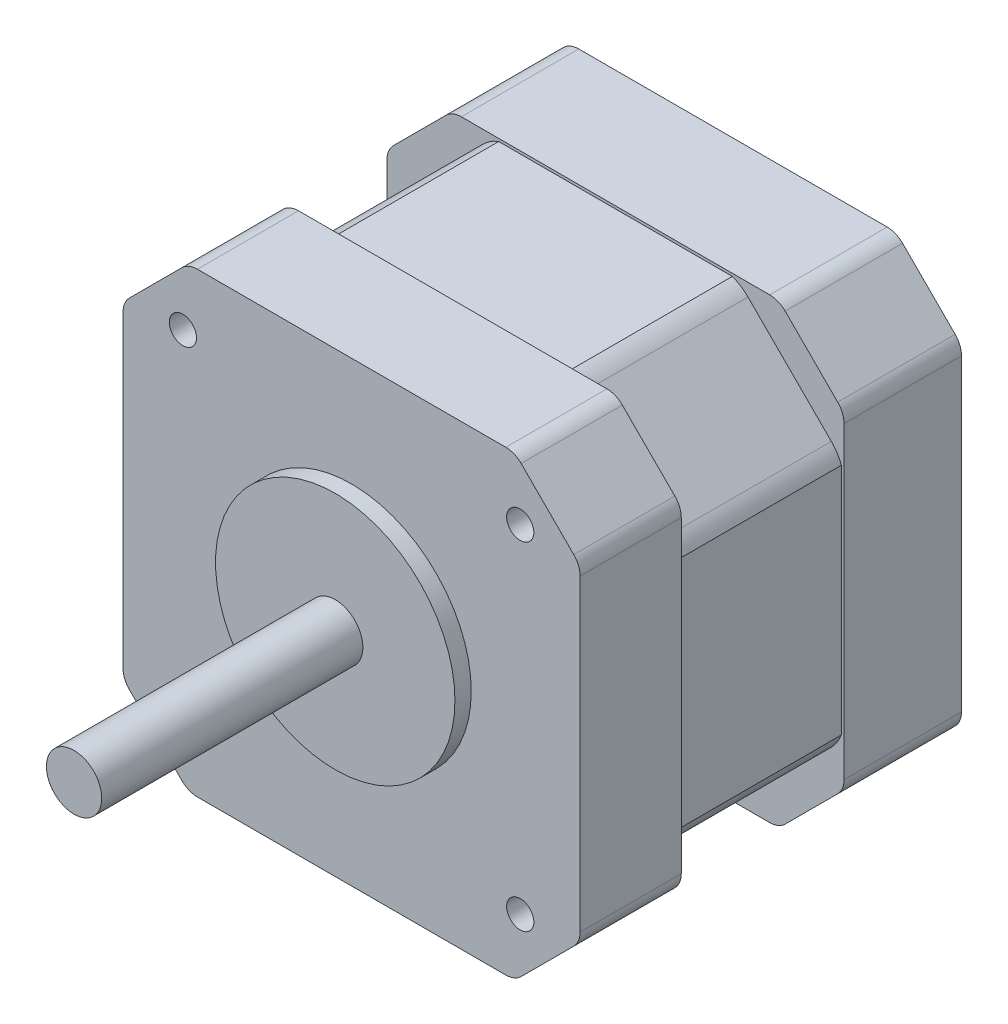
SolidWorks part; units mm, degrees
ref_plane "Front Plane" through (0, 0, 0) normal (0, 0, 1) x (1, 0, 0)
ref_plane "Top Plane" through (0, 0, 0) normal (0, 1, 0) x (1, 0, 0)
ref_plane "Right Plane" through (0, 0, 0) normal (1, 0, 0) x (0, 0, -1)
ref_plane "Plane1" through (0, 0, 8) normal (0, 0, 1) x (1, 0, 0)
sketch "Sketch1" plane through (0, 0, 8) normal (0, 0, 1) x (1, 0, 0)
  line L0 (-21, 15) -> (-21, -15)
  line L1 (-21, -15) -> (-15, -21)
  line L2 (-15, -21) -> (15, -21)
  line L3 (15, -21) -> (21, -15)
  line L4 (21, -15) -> (21, 15)
  line L5 (21, 15) -> (15, 21)
  line L6 (15, 21) -> (-15, 21)
  line L7 (-15, 21) -> (-21, 15)
extrude "Boss-Extrude1" add sketch "Sketch1" against normal blind 9.2964
sketch "Sketch2" plane through (0, 0, -1.2964) normal (0, 0, -1) x (-1, 0, 0)
  line L0 (-10.7351, 20.75) -> (10.7351, 20.75)
  line L1 (12.1716, 19.8284) -> (19.8284, 12.1716)
  line L2 (20.75, 10.7351) -> (20.75, -10.7351)
  line L3 (19.8284, -12.1716) -> (12.1716, -19.8284)
  line L4 (10.7351, -20.75) -> (-10.7351, -20.75)
  line L5 (-12.1716, -19.8284) -> (-19.8284, -12.1716)
  line L6 (-20.75, -10.7351) -> (-20.75, 10.7351)
  line L7 (-19.8284, 12.1716) -> (-12.1716, 19.8284)
  arc A0 (-12.1716, 19.8284) -> (-10.7351, 20.75) centre (-9.3431, 17) cw
  arc A1 (10.7351, 20.75) -> (12.1716, 19.8284) centre (9.3431, 17) cw
  arc A2 (19.8284, 12.1716) -> (20.75, 10.7351) centre (17, 9.3431) cw
  arc A3 (20.75, -10.7351) -> (19.8284, -12.1716) centre (17, -9.3431) cw
  arc A4 (12.1716, -19.8284) -> (10.7351, -20.75) centre (9.3431, -17) cw
  arc A5 (-10.7351, -20.75) -> (-12.1716, -19.8284) centre (-9.3431, -17) cw
  arc A6 (-19.8284, -12.1716) -> (-20.75, -10.7351) centre (-17, -9.3431) cw
  arc A7 (-20.75, 10.7351) -> (-19.8284, 12.1716) centre (-17, 9.3431) cw
extrude "Boss-Extrude2" add sketch "Sketch2" along normal blind 16.002
ref_plane "Plane2" through (0, 0, -16.256) normal (0, 0, 1) x (1, 0, 0)
sketch "Sketch3" plane through (0, 0, -16.256) normal (0, 0, 1) x (1, 0, 0)
  line L0 (-21, 15) -> (-21, -15)
  line L1 (-21, -15) -> (-15, -21)
  line L2 (-15, -21) -> (15, -21)
  line L3 (15, -21) -> (21, -15)
  line L4 (21, -15) -> (21, 15)
  line L5 (21, 15) -> (15, 21)
  line L6 (15, 21) -> (-15, 21)
  line L7 (-15, 21) -> (-21, 15)
extrude "Boss-Extrude3" add sketch "Sketch3" against normal blind 10.795
sketch "Sketch4" plane through (0, 0, 8) normal (0, 0, 1) x (1, 0, 0)
  circle A0 centre (0, 0) radius 11
extrude "Boss-Extrude4" add sketch "Sketch4" along normal blind 1.5
sketch "Sketch5" plane through (0, 0, 9.5) normal (0, 0, 1) x (1, 0, 0)
  circle A0 centre (0, 0) radius 2.54
  dimension "D1" = 5.08
extrude "Boss-Extrude5" add sketch "Sketch5" along normal blind 24
hole_wizard "#2 Clearance Hole1" positions "Sketch8" profile "Sketch7" hole size "#2" standard "ANSI Inch"
sketch "Sketch8" plane through (0, 0, 8) normal (0, 0, 1) x (1, 0, 0)
  point P0 (-15.5, 15.5)
  point P1 (15.5, 15.5)
  point P2 (-15.5, -15.5)
  point P3 (15.5, -15.5)
sketch "Sketch7" plane through (-15.5, 15.5, 8) normal (1, 0, 0) x (0, -1, 0)
  line L0 (0, 0) -> (0, 6.7511)
  line L1 (0, 6.7511) -> (1.25, 6)
  line L2 (1.25, 6) -> (1.25, 0)
  line L5 (1.25, 0) -> (0, 0)
  line L10 (0, 6.7511) -> (-1.25, 6) construction
  line L11 (0, -6.35) -> (0, 107.95) construction
  dimension "Hole Dia." = 2.5
  dimension "Hole Depth" = 6
  dimension "Drill Angle" = 118
fillet "Fillet1" radius 2 16 edges at (-21, -15, -21.6535) (21, -15, -21.6535) (15, 21, -21.6535) (-15, 21, 3.3518) (-15, -21, -21.6535) (-21, 15, 3.3518) (-15, 21, -21.6535) (21, 15, 3.3518) (21, 15, -21.6535) (-21, -15, 3.3518) (15, -21, -21.6535) (-15, -21, 3.3518) (-21, 15, -21.6535) (21, -15, 3.3518) (15, 21, 3.3518) (15, -21, 3.3518)
